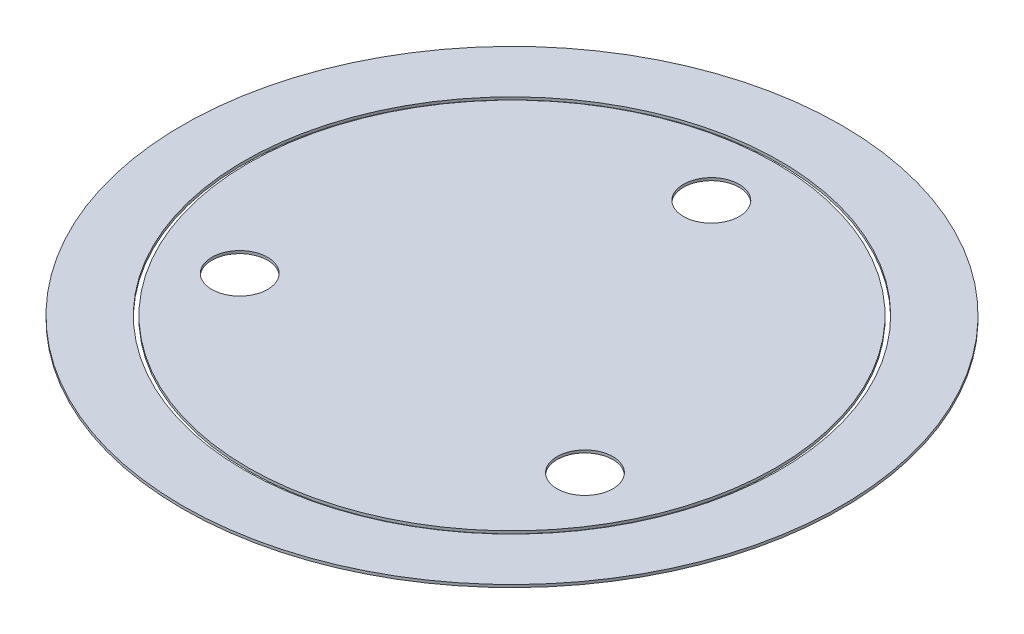
SolidWorks part; units mm, degrees
ref_plane "Front Plane" through (0, 0, 0) normal (0, 0, 1) x (1, 0, 0)
ref_plane "Top Plane" through (0, 0, 0) normal (0, 1, 0) x (1, 0, 0)
ref_plane "Right Plane" through (0, 0, 0) normal (1, 0, 0) x (0, 0, -1)
sketch "Sketch1" plane through (0, 0, 0) normal (0, 1, 0) x (1, 0, 0)
  line L0 (0, 0) -> (0, 19.85) construction
  line L1 (0, 0) -> (17.1906, -9.925) construction
  line L2 (0, 0) -> (-17.1906, -9.925) construction
  circle A0 centre (0, 0) radius 24.8
  circle A1 centre (0, 0) radius 20.15
  circle A3 centre (0, 0) radius 19.85
  circle A4 centre (0, 0) radius 15 construction
  circle A5 centre (0, 15) radius 2.1
  circle A6 centre (12.9904, -7.5) radius 2.1
  circle A7 centre (-12.9904, -7.5) radius 2.1
  point P15 (0, 0)
  point P16 (0, 0)
  point P17 (0, 0)
  dimension "D1" = 49.6
  dimension "D2" = 40.3
  dimension "D3" = 39.7
  dimension "D6" = 30
  dimension "D7" = 4.2
  dimension "D4" = 120
  dimension "D5" = 120
extrude "Boss-Extrude1" add sketch "Sketch1" along normal blind 0.2 contours A0 A1 | A3 A7 A6 A5
